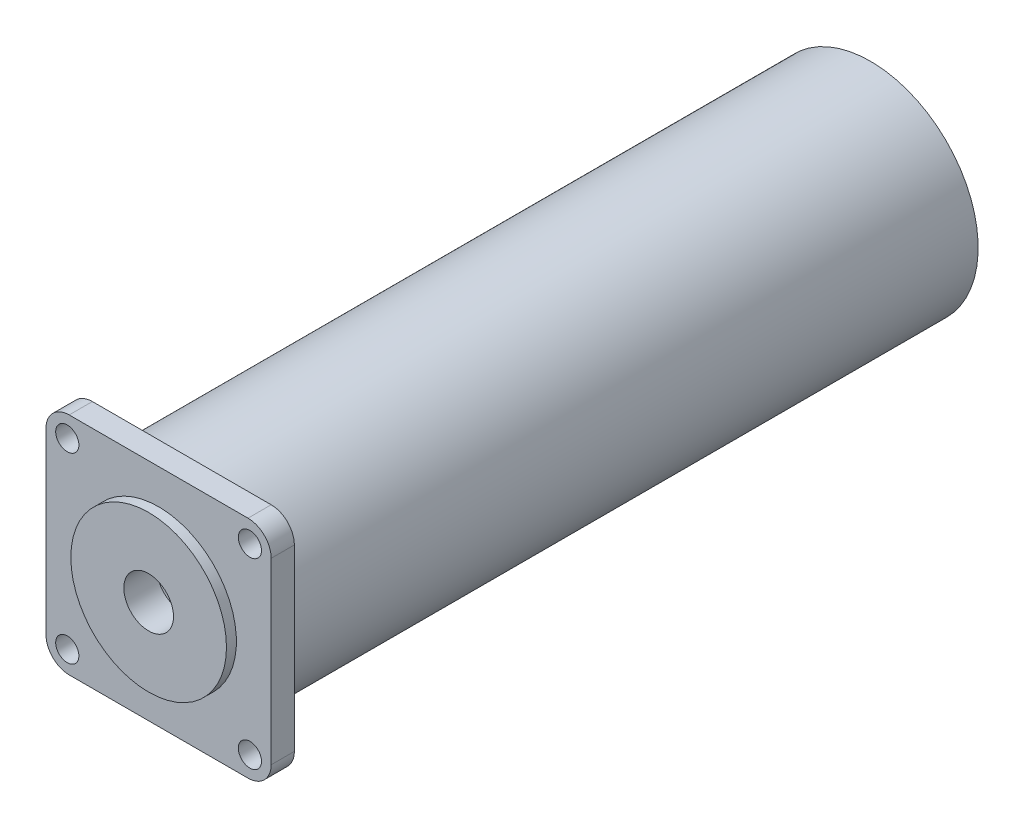
SolidWorks part; units mm, degrees
ref_plane "Frontal Plane" through (0, 0, 0) normal (0, 0, 1) x (1, 0, 0)
ref_plane "Horizontal Plane" through (0, 0, 0) normal (0, 1, 0) x (1, 0, 0)
ref_plane "Profile Plane" through (0, 0, 0) normal (1, 0, 0) x (0, 0, -1)
sketch "Sketch1" plane through (0, 0, 0) normal (0, 0, 1) x (1, 0, 0)
  line L1 (-27, -34) -> (27, -34)
  line L2 (-34, -27) -> (-34, 27)
  line L3 (-27, 34) -> (27, 34)
  line L4 (34, -27) -> (34, 27)
  line L5 (-34, -34) -> (34, 34) construction
  line L6 (-34, 34) -> (34, -34) construction
  arc A0 (-27, -34) -> (-34, -27) centre (-27, -27) cw
  arc A1 (27, -34) -> (34, -27) centre (27, -27) ccw
  arc A2 (27, 34) -> (34, 27) centre (27, 27) cw
  arc A3 (-34, 27) -> (-27, 34) centre (-27, 27) cw
  circle A4 centre (0, 0) radius 7.5
  circle A5 centre (27.5772, 27.5772) radius 3.5
  circle A6 centre (-27.5772, 27.5772) radius 3.5
  circle A7 centre (0, 0) radius 39 construction
  circle A8 centre (-27.5772, -27.5772) radius 3.5
  circle A9 centre (27.5772, -27.5772) radius 3.5
  point P0 (0, 0)
  dimension "D3" = 7
  dimension "D4" = 15
  dimension "D5" = 78
  dimension "D6" = 7
  dimension "D1" = 68
  dimension "D2" = 68
extrude "Boss-Extrude1" add sketch "Sketch1" against normal blind 7
ref_plane "Plane1" through (0, 0, -7) normal (0, 0, -1) x (-1, 0, 0)
sketch "Sketch2" plane through (0, 0, -7) normal (0, 0, -1) x (-1, 0, 0)
  circle A0 centre (0, 0) radius 32.5
  dimension "D1" = 65
extrude "Boss-Extrude2" add sketch "Sketch2" along normal blind 208
ref_plane "Plane2" through (0, 0, 0) normal (0, 0, 1) x (1, 0, 0)
sketch "Sketch3" plane through (0, 0, 0) normal (0, 0, 1) x (1, 0, 0)
  circle A0 centre (0, 0) radius 7.5
  circle A1 centre (0, 0) radius 23.5
  dimension "D1" = 15
  dimension "D2" = 47
extrude "Boss-Extrude3" add sketch "Sketch3" along normal blind 3
equation "\"WallThickness\"= 0.5cm"
equation "\"Box-X\"= 40cm"
equation "\"Box-Z\"= 20cm"
equation "\"Box-Y\"= 30cm"
equation "\"BottomPlateX\"= 3ft"
equation "\"ArmPlateX\"= 18in"
equation "\"D1@Sketch1\"=\"DCMotor2X\""
equation "\"D2@Sketch1\"=\"DCMotor2X\""
equation "\"D1@Sketch2\"=\"DCMotor2D\""
equation "\"DCMotor2L\"= 208mm"
equation "\"D1@Boss-Extrude2\"=\"DCMotor2L\"-7mm"
equation "\"D4@Sketch1\"=\"DCMotor2ShaftD\""
equation "\"DCMotor2D\"= 65mm"
equation "\"DCMotor2ShaftL\"= 39mm"
equation "\"DCMotor2X\"= 68mm"
equation "\"ArmPlateThickness\"= .125in"
equation "\"DCMotor1D\"= 65mm"
equation "\"DCMotor1L\"= 215mm"
equation "\"DCMotor1ShaftL\"= 30mm"
equation "\"BenchDepth\"= 5cm"
equation "\"BenchH\"= 10cm"
equation "\"BenchL\"= 15cm"
equation "\"ActuatorPinD\"= 6.35mm"
equation "\"ActuatorPinL\"= 15cm"
equation "\"DCMotor2ShaftD\"= 15mm"
equation "\"PillowBlockW\"= 5cm"
equation "\"PillowBlockCenterH\"= \"DCMotor2X\"/2"
equation "\"EncoderRadius\"= 19mm"
equation "\"EncoderShaftL\"= 15mm"
equation "\"EncoderL\"= 33mm"
equation "\"EncoderHousingThickness\"= 7.5mm"
equation "\"D1@Sketch3\"=\"DCMotor2ShaftD\""
equation "\"D2@Sketch3\"=47"
